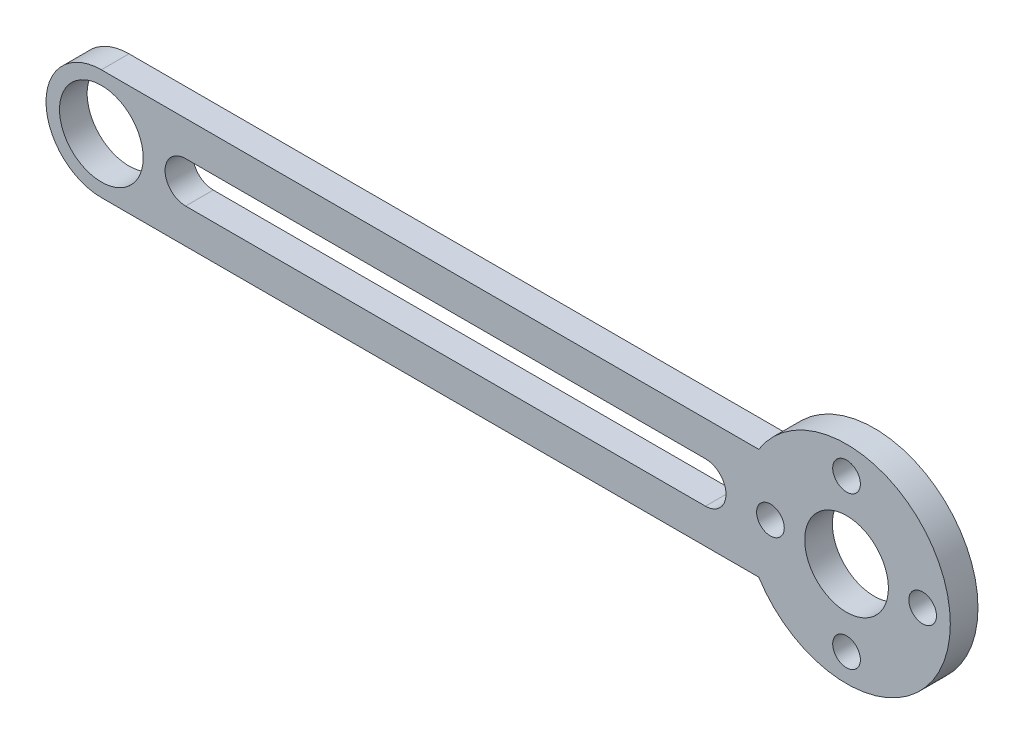
SolidWorks part; units mm, degrees
ref_plane "前视基准面" through (0, 0, 0) normal (0, 0, 1) x (1, 0, 0)
ref_plane "上视基准面" through (0, 0, 0) normal (0, 1, 0) x (1, 0, 0)
ref_plane "右视基准面" through (0, 0, 0) normal (1, 0, 0) x (0, 0, -1)
sketch "草图1" plane through (0, 0, 0) normal (0, 0, 1) x (1, 0, 0)
  line L0 (-53.8502, 4) -> (-6.3443, 4)
  line L1 (-53.8502, -4) -> (-6.3443, -4)
  line L2 (-47.7619, 0) -> (-10.1946, 0) construction
  line L3 (-47.7619, 1.4835) -> (-10.1946, 1.4835)
  line L4 (-47.7619, -1.4835) -> (-10.1946, -1.4835)
  circle A0 centre (0, 0) radius 1.5
  arc A1 (-6.3443, -4) -> (-6.3443, 4) centre (0, 0) ccw
  circle A2 centre (-5.5, 0) radius 1
  circle A3 centre (5.5, 0) radius 1
  arc A4 (-53.8502, 4) -> (-53.8502, -4) centre (-53.8502, 0) ccw
  circle A5 centre (-53.8502, 0) radius 3.025
  circle A6 centre (0, -5.5) radius 1
  circle A7 centre (-5.5, 0) radius 1
  circle A8 centre (0, 5.5) radius 1
  arc A9 (-47.7619, 1.4835) -> (-47.7619, -1.4835) centre (-47.7619, 0) ccw
  arc A10 (-10.1946, -1.4835) -> (-10.1946, 1.4835) centre (-10.1946, 0) ccw
  point P15 (-28.9782, 0)
  point P22 (0, 0)
  dimension "D1" = 3
  dimension "D2" = 15
  dimension "D3" = 2
  dimension "D4" = 2
  dimension "D5" = 5.5
  dimension "D7" = 8
  dimension "D8" = 6.05
  dimension "D6" = 5.5
  dimension "D9" = 4
extrude "凸台-拉伸1" add sketch "草图1" along normal blind 2 contours L0 A4 L1 A1 A10 L4 A9 L3 A8 A6 A5 A0 A2 A3
sketch "草图2" plane through (0, 0, 2) normal (0, 0, 1) x (1, 0, 0)
  circle A0 centre (0, 0) radius 3.025
  dimension "D1" = 6.05
extrude "切除-拉伸1" cut sketch "草图2" against normal blind 10
